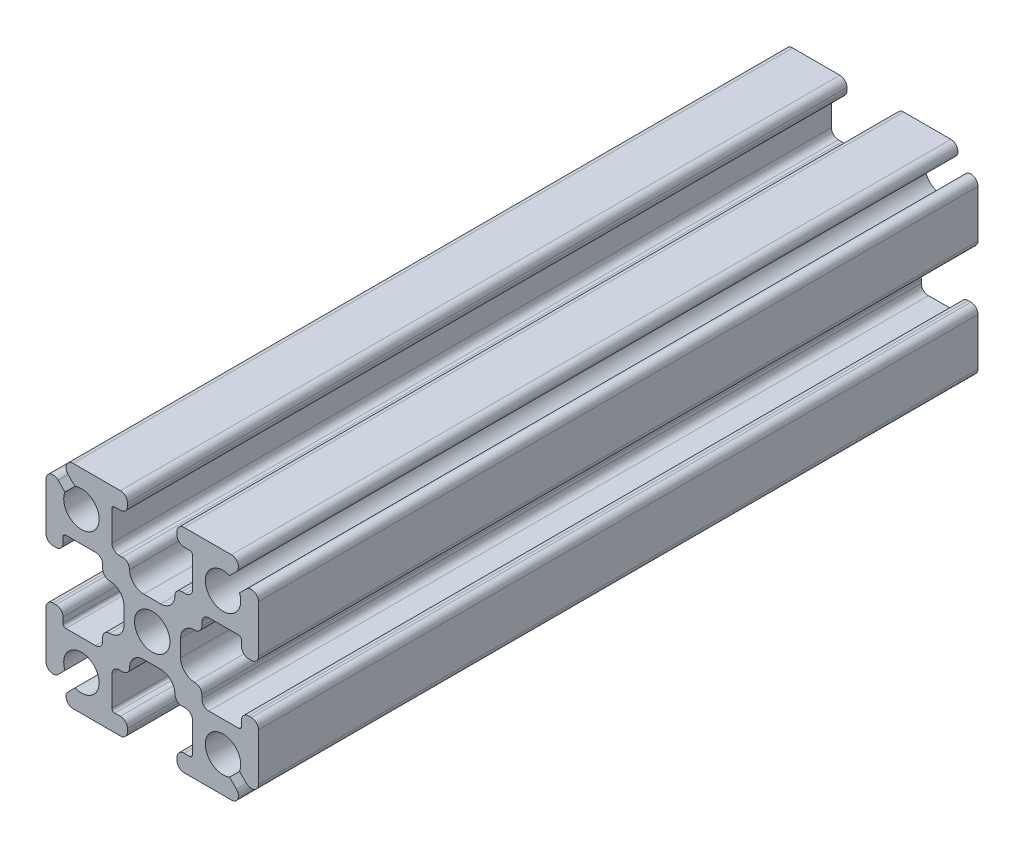
SolidWorks part; units mm, degrees
ref_plane "Front Plane" through (0, 0, 0) normal (0, 0, 1) x (1, 0, 0)
ref_plane "Top Plane" through (0, 0, 0) normal (0, 1, 0) x (1, 0, 0)
ref_plane "Right Plane" through (0, 0, 0) normal (1, 0, 0) x (0, 0, -1)
sketch "Sketch1" plane through (0, 0, 0) normal (0, 0, 1) x (1, 0, 0)
  line L0 (6.6464, 5.9393) -> (6.1636, 5.4565)
  line L1 (5.4565, 6.1636) -> (5.9393, 6.6464)
  line L2 (5.5858, 7.5) -> (2.25, 7.5)
  line L3 (1.75, 7) -> (1.75, 6.8)
  line L4 (2.25, 6.3) -> (2.65, 6.3)
  line L5 (2.85, 6.1) -> (2.85, 4)
  line L6 (2.35, 3.5) -> (2.1, 3.5)
  line L7 (0.6, 2) -> (-0.6, 2)
  line L8 (-2.1, 3.5) -> (-2.35, 3.5)
  line L9 (-2.85, 4) -> (-2.85, 6.1)
  line L10 (-2.65, 6.3) -> (-2.25, 6.3)
  line L11 (-1.75, 6.8) -> (-1.75, 7)
  line L12 (-2.25, 7.5) -> (-5.5858, 7.5)
  line L13 (-5.9393, 6.6464) -> (-5.4565, 6.1636)
  line L14 (-6.1636, 5.4565) -> (-6.6464, 5.9393)
  line L15 (-7.5, 5.5858) -> (-7.5, 2.25)
  line L16 (-7, 1.75) -> (-6.8, 1.75)
  line L17 (-6.3, 2.25) -> (-6.3, 2.65)
  line L18 (-6.1, 2.85) -> (-4, 2.85)
  line L19 (-3.5, 2.35) -> (-3.5, 2.1)
  line L20 (-2, 0.6) -> (-2, -0.6)
  line L21 (-3.5, -2.1) -> (-3.5, -2.35)
  line L22 (-4, -2.85) -> (-6.1, -2.85)
  line L23 (-6.3, -2.65) -> (-6.3, -2.25)
  line L24 (-6.8, -1.75) -> (-7, -1.75)
  line L25 (-7.5, -2.25) -> (-7.5, -5.5858)
  line L26 (-6.6464, -5.9393) -> (-6.1636, -5.4565)
  line L27 (-5.4565, -6.1636) -> (-5.9393, -6.6464)
  line L28 (-5.5858, -7.5) -> (-2.25, -7.5)
  line L29 (-1.75, -7) -> (-1.75, -6.8)
  line L30 (-2.25, -6.3) -> (-2.65, -6.3)
  line L31 (-2.85, -6.1) -> (-2.85, -4)
  line L32 (-2.35, -3.5) -> (-2.1, -3.5)
  line L33 (-0.6, -2) -> (0.6, -2)
  line L34 (2.1, -3.5) -> (2.35, -3.5)
  line L35 (2.85, -4) -> (2.85, -6.1)
  line L36 (2.65, -6.3) -> (2.25, -6.3)
  line L37 (1.75, -6.8) -> (1.75, -7)
  line L38 (2.25, -7.5) -> (5.5858, -7.5)
  line L39 (5.9393, -6.6464) -> (5.4565, -6.1636)
  line L40 (6.1636, -5.4565) -> (6.6464, -5.9393)
  line L41 (7.5, -5.5858) -> (7.5, -2.25)
  line L42 (7, -1.75) -> (6.8, -1.75)
  line L43 (6.3, -2.25) -> (6.3, -2.65)
  line L44 (6.1, -2.85) -> (4, -2.85)
  line L45 (3.5, -2.35) -> (3.5, -2.1)
  line L46 (2, -0.6) -> (2, 0.6)
  line L47 (3.5, 2.1) -> (3.5, 2.35)
  line L48 (4, 2.85) -> (6.1, 2.85)
  line L49 (6.3, 2.65) -> (6.3, 2.25)
  line L50 (6.8, 1.75) -> (7, 1.75)
  line L51 (7.5, 2.25) -> (7.5, 5.5858)
  circle A0 centre (0, 0) radius 1.25
  arc A1 (6.1636, 5.4565) -> (5.4565, 6.1636) centre (5, 5) cw
  arc A2 (5.9393, 6.6464) -> (5.5858, 7.5) centre (5.5858, 7) ccw
  arc A3 (2.25, 7.5) -> (1.75, 7) centre (2.25, 7) ccw
  arc A4 (1.75, 6.8) -> (2.25, 6.3) centre (2.25, 6.8) ccw
  arc A5 (2.65, 6.3) -> (2.85, 6.1) centre (2.65, 6.1) cw
  arc A6 (2.85, 4) -> (2.35, 3.5) centre (2.35, 4) cw
  arc A7 (2.1, 3.5) -> (1.6, 3) centre (2.1, 3) ccw
  arc A8 (1.6, 3) -> (0.6, 2) centre (0.6, 3) cw
  arc A9 (-0.6, 2) -> (-1.6, 3) centre (-0.6, 3) cw
  arc A10 (-1.6, 3) -> (-2.1, 3.5) centre (-2.1, 3) ccw
  arc A11 (-2.35, 3.5) -> (-2.85, 4) centre (-2.35, 4) cw
  arc A12 (-2.85, 6.1) -> (-2.65, 6.3) centre (-2.65, 6.1) cw
  arc A13 (-2.25, 6.3) -> (-1.75, 6.8) centre (-2.25, 6.8) ccw
  arc A14 (-1.75, 7) -> (-2.25, 7.5) centre (-2.25, 7) ccw
  arc A15 (-5.5858, 7.5) -> (-5.9393, 6.6464) centre (-5.5858, 7) ccw
  arc A16 (-5.4565, 6.1636) -> (-6.1636, 5.4565) centre (-5, 5) cw
  arc A17 (-6.6464, 5.9393) -> (-7.5, 5.5858) centre (-7, 5.5858) ccw
  arc A18 (-7.5, 2.25) -> (-7, 1.75) centre (-7, 2.25) ccw
  arc A19 (-6.8, 1.75) -> (-6.3, 2.25) centre (-6.8, 2.25) ccw
  arc A20 (-6.3, 2.65) -> (-6.1, 2.85) centre (-6.1, 2.65) cw
  arc A21 (-4, 2.85) -> (-3.5, 2.35) centre (-4, 2.35) cw
  arc A22 (-3.5, 2.1) -> (-3, 1.6) centre (-3, 2.1) ccw
  arc A23 (-3, 1.6) -> (-2, 0.6) centre (-3, 0.6) cw
  arc A24 (-2, -0.6) -> (-3, -1.6) centre (-3, -0.6) cw
  arc A25 (-3, -1.6) -> (-3.5, -2.1) centre (-3, -2.1) ccw
  arc A26 (-3.5, -2.35) -> (-4, -2.85) centre (-4, -2.35) cw
  arc A27 (-6.1, -2.85) -> (-6.3, -2.65) centre (-6.1, -2.65) cw
  arc A28 (-6.3, -2.25) -> (-6.8, -1.75) centre (-6.8, -2.25) ccw
  arc A29 (-7, -1.75) -> (-7.5, -2.25) centre (-7, -2.25) ccw
  arc A30 (-7.5, -5.5858) -> (-6.6464, -5.9393) centre (-7, -5.5858) ccw
  arc A31 (-6.1636, -5.4565) -> (-5.4565, -6.1636) centre (-5, -5) cw
  arc A32 (-5.9393, -6.6464) -> (-5.5858, -7.5) centre (-5.5858, -7) ccw
  arc A33 (-2.25, -7.5) -> (-1.75, -7) centre (-2.25, -7) ccw
  arc A34 (-1.75, -6.8) -> (-2.25, -6.3) centre (-2.25, -6.8) ccw
  arc A35 (-2.65, -6.3) -> (-2.85, -6.1) centre (-2.65, -6.1) cw
  arc A36 (-2.85, -4) -> (-2.35, -3.5) centre (-2.35, -4) cw
  arc A37 (-2.1, -3.5) -> (-1.6, -3) centre (-2.1, -3) ccw
  arc A38 (-1.6, -3) -> (-0.6, -2) centre (-0.6, -3) cw
  arc A39 (0.6, -2) -> (1.6, -3) centre (0.6, -3) cw
  arc A40 (1.6, -3) -> (2.1, -3.5) centre (2.1, -3) ccw
  arc A41 (2.35, -3.5) -> (2.85, -4) centre (2.35, -4) cw
  arc A42 (2.85, -6.1) -> (2.65, -6.3) centre (2.65, -6.1) cw
  arc A43 (2.25, -6.3) -> (1.75, -6.8) centre (2.25, -6.8) ccw
  arc A44 (1.75, -7) -> (2.25, -7.5) centre (2.25, -7) ccw
  arc A45 (5.5858, -7.5) -> (5.9393, -6.6464) centre (5.5858, -7) ccw
  arc A46 (5.4565, -6.1636) -> (6.1636, -5.4565) centre (5, -5) cw
  arc A47 (6.6464, -5.9393) -> (7.5, -5.5858) centre (7, -5.5858) ccw
  arc A48 (7.5, -2.25) -> (7, -1.75) centre (7, -2.25) ccw
  arc A49 (6.8, -1.75) -> (6.3, -2.25) centre (6.8, -2.25) ccw
  arc A50 (6.3, -2.65) -> (6.1, -2.85) centre (6.1, -2.65) cw
  arc A51 (4, -2.85) -> (3.5, -2.35) centre (4, -2.35) cw
  arc A52 (3.5, -2.1) -> (3, -1.6) centre (3, -2.1) ccw
  arc A53 (3, -1.6) -> (2, -0.6) centre (3, -0.6) cw
  arc A54 (2, 0.6) -> (3, 1.6) centre (3, 0.6) cw
  arc A55 (3, 1.6) -> (3.5, 2.1) centre (3, 2.1) ccw
  arc A56 (3.5, 2.35) -> (4, 2.85) centre (4, 2.35) cw
  arc A57 (6.1, 2.85) -> (6.3, 2.65) centre (6.1, 2.65) cw
  arc A58 (6.3, 2.25) -> (6.8, 1.75) centre (6.8, 2.25) ccw
  arc A59 (7, 1.75) -> (7.5, 2.25) centre (7, 2.25) ccw
  arc A60 (7.5, 5.5858) -> (6.6464, 5.9393) centre (7, 5.5858) ccw
extrude "Boss-Extrude1" add sketch "Sketch1" along normal blind 50.8
